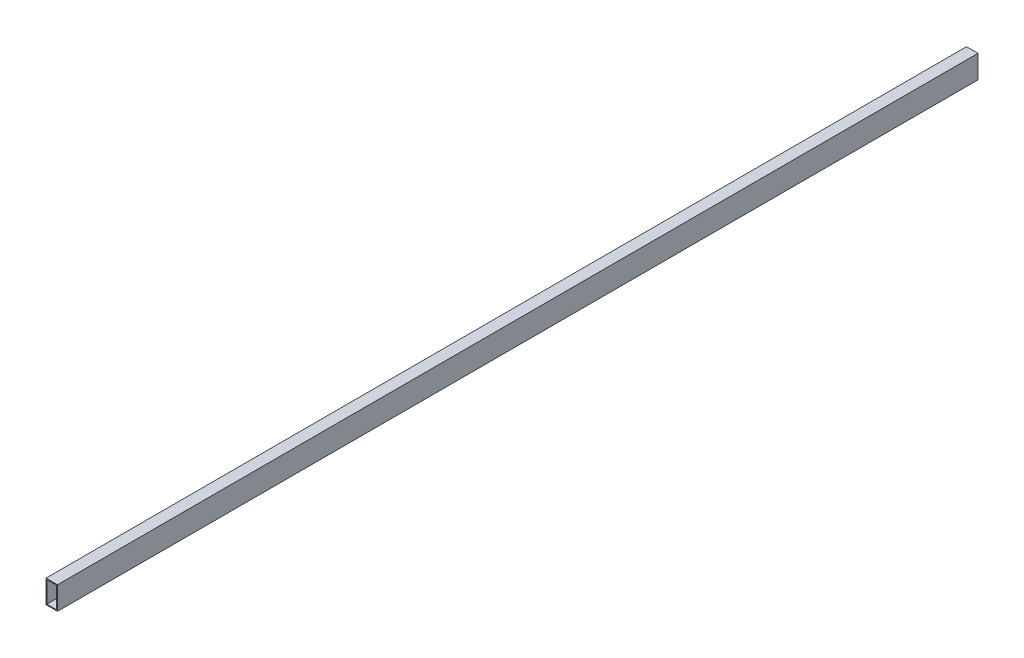
SolidWorks part; units mm, degrees
ref_plane "Alzado" through (0, 0, 0) normal (0, 0, 1) x (1, 0, 0)
ref_plane "Planta" through (0, 0, 0) normal (0, 1, 0) x (1, 0, 0)
ref_plane "Vista lateral" through (0, 0, 0) normal (1, 0, 0) x (0, 0, -1)
sketch "Croquis1" plane through (0, 0, 0) normal (0, 0, 1) x (1, 0, 0)
  line L0 (21, 46) -> (-21, 46)
  line L1 (25, -50) -> (-25, -50)
  line L2 (25, -50) -> (25, 50)
  line L3 (25, 50) -> (-25, 50)
  line L4 (-25, -50) -> (-25, 50)
  line L5 (25, -50) -> (-25, 50) construction
  line L6 (25, 50) -> (-25, -50) construction
  line L7 (-21, -46) -> (-21, 46)
  line L8 (21, -46) -> (-21, -46)
  line L9 (21, -46) -> (21, 46)
  point P0 (0, 0)
  dimension "D1" = 100
  dimension "D2" = 50
  dimension "D3" = 4
extrude "Saliente-Extruir1" add sketch "Croquis1" along normal blind 4000 contours L3 L4 L1 L2
